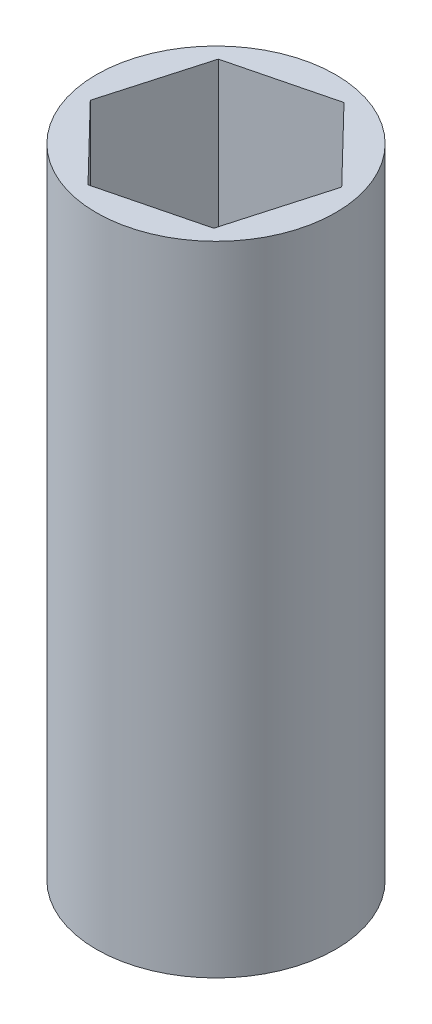
SolidWorks part; units mm, degrees
ref_plane "Front Plane" through (0, 0, 0) normal (0, 0, 1) x (1, 0, 0)
ref_plane "Top Plane" through (0, 0, 0) normal (0, 1, 0) x (1, 0, 0)
ref_plane "Right Plane" through (0, 0, 0) normal (1, 0, 0) x (0, 0, -1)
sketch "Sketch1" plane through (0, 0, 0) normal (0, 1, 0) x (1, 0, 0)
  line L1 (1.5057, 5.2891) -> (-3.8277, 3.9485)
  line L2 (-3.8277, 3.9485) -> (-5.3333, -1.3406)
  line L3 (-5.3333, -1.3406) -> (-1.5057, -5.2891)
  line L4 (-1.5057, -5.2891) -> (3.8277, -3.9485)
  line L5 (3.8277, -3.9485) -> (5.3333, 1.3406)
  line L6 (5.3333, 1.3406) -> (1.5057, 5.2891)
  circle A0 centre (0, 0) radius 4.7625 construction
  circle A1 centre (0, 0) radius 6.35
  dimension "D2" = 12.7
  dimension "D1" = 9.525
extrude "Boss-Extrude1" add sketch "Sketch1" along normal blind 33.8667
